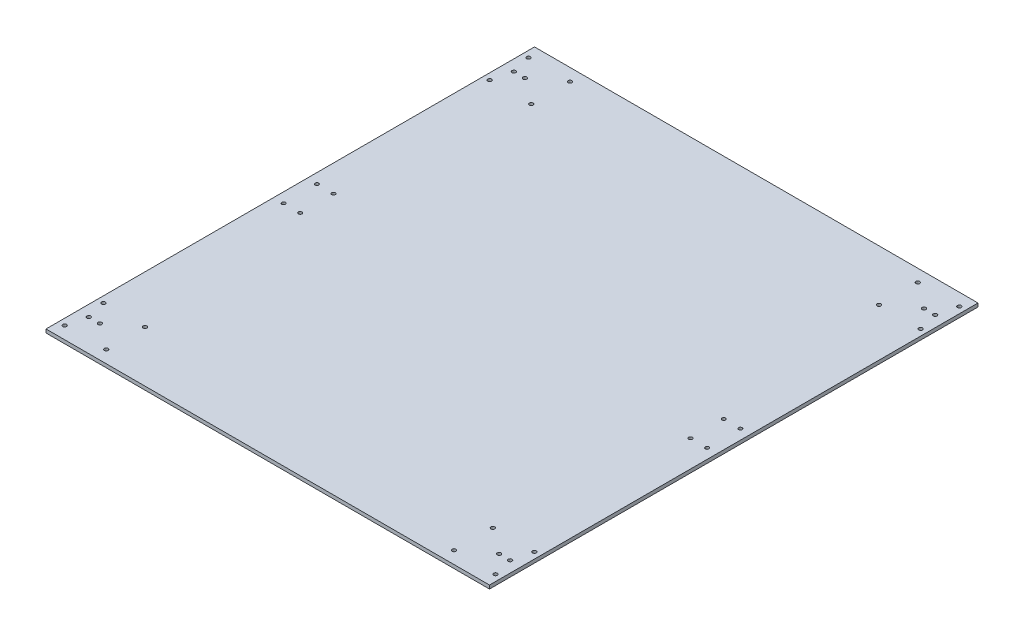
SolidWorks part; units mm, degrees
material "Acrylic (Medium-high impact)"
ref_plane "Front Plane" through (0, 0, 0) normal (0, 0, 1) x (1, 0, 0)
ref_plane "Top Plane" through (0, 0, 0) normal (0, 1, 0) x (1, 0, 0)
ref_plane "Right Plane" through (0, 0, 0) normal (1, 0, 0) x (0, 0, -1)
sketch "Sketch1" plane through (0, 0, 0) normal (0, 1, 0) x (1, 0, 0)
  line L1 (-200, 220.3) -> (200, 220.3)
  line L2 (-200, 220.3) -> (-200, -220.3)
  line L3 (-200, -220.3) -> (200, -220.3)
  line L4 (200, 220.3) -> (200, -220.3)
  line L5 (-200, 220.3) -> (200, -220.3) construction
  line L6 (-200, -220.3) -> (200, 220.3) construction
  point P0 (0, 0)
  dimension "D1" = 400
  dimension "D2" = 440.6
extrude "Boss-Extrude1" add sketch "Sketch1" along normal blind 3.175 contours L2 L3 L4 L1
sketch "Sketch2" plane through (0, 3.175, 0) normal (0, 1, 0) x (1, 0, 0)
  arc A0 (-181.7, 191.65) -> (-181.6248, 191.15) centre (-180, 191.65) ccw construction
  arc A1 (-181.6248, 192.15) -> (-181.7, 191.65) centre (-180, 191.65) ccw construction
  arc A2 (-178.3752, 192.15) -> (-181.6248, 192.15) centre (-180, 191.65) ccw construction
  arc A3 (-178.3, 191.65) -> (-178.3752, 192.15) centre (-180, 191.65) ccw construction
  arc A4 (-178.3752, 191.15) -> (-178.3, 191.65) centre (-180, 191.65) ccw construction
  arc A5 (-181.6248, 191.15) -> (-178.3752, 191.15) centre (-180, 191.65) ccw construction
  arc A6 (-188.3752, 192.15) -> (-191.6248, 192.15) centre (-190, 191.65) ccw construction
  arc A7 (-188.3, 191.65) -> (-188.3752, 192.15) centre (-190, 191.65) ccw construction
  arc A8 (-188.3752, 191.15) -> (-188.3, 191.65) centre (-190, 191.65) ccw construction
  arc A9 (-191.6248, 191.15) -> (-188.3752, 191.15) centre (-190, 191.65) ccw construction
  arc A10 (-191.7, 191.65) -> (-191.6248, 191.15) centre (-190, 191.65) ccw construction
  arc A11 (-191.6248, 192.15) -> (-191.7, 191.65) centre (-190, 191.65) ccw construction
  circle A12 centre (-156.8618, 174.15) radius 1.7 construction
  circle A13 centre (-194.3382, 174.15) radius 1.7 construction
  circle A14 centre (-156.8618, 209.15) radius 1.7 construction
  circle A15 centre (-194.3382, 209.15) radius 1.7 construction
  arc A16 (-181.7, 191.65) -> (-181.6248, 191.15) centre (-180, 191.65) ccw
  arc A17 (-181.6248, 192.15) -> (-181.7, 191.65) centre (-180, 191.65) ccw
  arc A18 (-178.3752, 192.15) -> (-181.6248, 192.15) centre (-180, 191.65) ccw
  arc A19 (-178.3, 191.65) -> (-178.3752, 192.15) centre (-180, 191.65) ccw
  arc A20 (-178.3752, 191.15) -> (-178.3, 191.65) centre (-180, 191.65) ccw
  arc A21 (-181.6248, 191.15) -> (-178.3752, 191.15) centre (-180, 191.65) ccw
  arc A22 (-188.3752, 192.15) -> (-191.6248, 192.15) centre (-190, 191.65) ccw
  arc A23 (-188.3, 191.65) -> (-188.3752, 192.15) centre (-190, 191.65) ccw
  arc A24 (-188.3752, 191.15) -> (-188.3, 191.65) centre (-190, 191.65) ccw
  arc A25 (-191.6248, 191.15) -> (-188.3752, 191.15) centre (-190, 191.65) ccw
  arc A26 (-191.7, 191.65) -> (-191.6248, 191.15) centre (-190, 191.65) ccw
  arc A27 (-191.6248, 192.15) -> (-191.7, 191.65) centre (-190, 191.65) ccw
  circle A28 centre (-156.8618, 174.15) radius 1.7
  circle A29 centre (-194.3382, 174.15) radius 1.7
  circle A30 centre (-156.8618, 209.15) radius 1.7
  circle A31 centre (-194.3382, 209.15) radius 1.7
  arc A32 (-178.3752, -192.15) -> (-178.3, -191.65) centre (-180, -191.65) ccw construction
  arc A33 (-181.6248, -192.15) -> (-178.3752, -192.15) centre (-180, -191.65) ccw construction
  arc A34 (-181.7, -191.65) -> (-181.6248, -192.15) centre (-180, -191.65) ccw construction
  arc A35 (-191.6248, -192.15) -> (-188.3752, -192.15) centre (-190, -191.65) ccw construction
  arc A36 (-188.3, -191.65) -> (-188.3752, -191.15) centre (-190, -191.65) ccw construction
  arc A37 (-188.3752, -192.15) -> (-188.3, -191.65) centre (-190, -191.65) ccw construction
  arc A38 (-191.7, -191.65) -> (-191.6248, -192.15) centre (-190, -191.65) ccw construction
  arc A39 (-191.6248, -191.15) -> (-191.7, -191.65) centre (-190, -191.65) ccw construction
  arc A40 (-178.3, -191.65) -> (-178.3752, -191.15) centre (-180, -191.65) ccw construction
  arc A41 (-181.6248, -191.15) -> (-181.7, -191.65) centre (-180, -191.65) ccw construction
  arc A42 (-178.3752, -191.15) -> (-181.6248, -191.15) centre (-180, -191.65) ccw construction
  arc A43 (-188.3752, -191.15) -> (-191.6248, -191.15) centre (-190, -191.65) ccw construction
  circle A44 centre (-156.8618, -209.15) radius 1.7 construction
  circle A45 centre (-194.3382, -209.15) radius 1.7 construction
  circle A46 centre (-156.8618, -174.15) radius 1.7 construction
  circle A47 centre (-194.3382, -174.15) radius 1.7 construction
  arc A48 (-178.3752, -192.15) -> (-178.3, -191.65) centre (-180, -191.65) ccw
  arc A49 (-181.6248, -192.15) -> (-178.3752, -192.15) centre (-180, -191.65) ccw
  arc A50 (-181.7, -191.65) -> (-181.6248, -192.15) centre (-180, -191.65) ccw
  arc A51 (-191.6248, -192.15) -> (-188.3752, -192.15) centre (-190, -191.65) ccw
  arc A52 (-188.3, -191.65) -> (-188.3752, -191.15) centre (-190, -191.65) ccw
  arc A53 (-188.3752, -192.15) -> (-188.3, -191.65) centre (-190, -191.65) ccw
  arc A54 (-191.7, -191.65) -> (-191.6248, -192.15) centre (-190, -191.65) ccw
  arc A55 (-191.6248, -191.15) -> (-191.7, -191.65) centre (-190, -191.65) ccw
  arc A56 (-178.3, -191.65) -> (-178.3752, -191.15) centre (-180, -191.65) ccw
  arc A57 (-181.6248, -191.15) -> (-181.7, -191.65) centre (-180, -191.65) ccw
  arc A58 (-178.3752, -191.15) -> (-181.6248, -191.15) centre (-180, -191.65) ccw
  arc A59 (-188.3752, -191.15) -> (-191.6248, -191.15) centre (-190, -191.65) ccw
  circle A60 centre (-156.8618, -209.15) radius 1.7
  circle A61 centre (-194.3382, -209.15) radius 1.7
  circle A62 centre (-156.8618, -174.15) radius 1.7
  circle A63 centre (-194.3382, -174.15) radius 1.7
  arc A64 (191.6248, -192.15) -> (191.7, -191.65) centre (190, -191.65) ccw construction
  arc A65 (188.3752, -192.15) -> (191.6248, -192.15) centre (190, -191.65) ccw construction
  arc A66 (188.3, -191.65) -> (188.3752, -192.15) centre (190, -191.65) ccw construction
  arc A67 (181.6248, -192.15) -> (181.7, -191.65) centre (180, -191.65) ccw construction
  arc A68 (178.3752, -192.15) -> (181.6248, -192.15) centre (180, -191.65) ccw construction
  arc A69 (178.3, -191.65) -> (178.3752, -192.15) centre (180, -191.65) ccw construction
  arc A70 (188.3752, -191.15) -> (188.3, -191.65) centre (190, -191.65) ccw construction
  arc A71 (191.7, -191.65) -> (191.6248, -191.15) centre (190, -191.65) ccw construction
  arc A72 (191.6248, -191.15) -> (188.3752, -191.15) centre (190, -191.65) ccw construction
  arc A73 (178.3752, -191.15) -> (178.3, -191.65) centre (180, -191.65) ccw construction
  arc A74 (181.7, -191.65) -> (181.6248, -191.15) centre (180, -191.65) ccw construction
  arc A75 (181.6248, -191.15) -> (178.3752, -191.15) centre (180, -191.65) ccw construction
  circle A76 centre (194.3382, -174.15) radius 1.7 construction
  circle A77 centre (156.8618, -174.15) radius 1.7 construction
  circle A78 centre (194.3382, -209.15) radius 1.7 construction
  circle A79 centre (156.8618, -209.15) radius 1.7 construction
  arc A80 (191.6248, -192.15) -> (191.7, -191.65) centre (190, -191.65) ccw
  arc A81 (188.3752, -192.15) -> (191.6248, -192.15) centre (190, -191.65) ccw
  arc A82 (188.3, -191.65) -> (188.3752, -192.15) centre (190, -191.65) ccw
  arc A83 (181.6248, -192.15) -> (181.7, -191.65) centre (180, -191.65) ccw
  arc A84 (178.3752, -192.15) -> (181.6248, -192.15) centre (180, -191.65) ccw
  arc A85 (178.3, -191.65) -> (178.3752, -192.15) centre (180, -191.65) ccw
  arc A86 (188.3752, -191.15) -> (188.3, -191.65) centre (190, -191.65) ccw
  arc A87 (191.7, -191.65) -> (191.6248, -191.15) centre (190, -191.65) ccw
  arc A88 (191.6248, -191.15) -> (188.3752, -191.15) centre (190, -191.65) ccw
  arc A89 (178.3752, -191.15) -> (178.3, -191.65) centre (180, -191.65) ccw
  arc A90 (181.7, -191.65) -> (181.6248, -191.15) centre (180, -191.65) ccw
  arc A91 (181.6248, -191.15) -> (178.3752, -191.15) centre (180, -191.65) ccw
  circle A92 centre (194.3382, -174.15) radius 1.7
  circle A93 centre (156.8618, -174.15) radius 1.7
  circle A94 centre (194.3382, -209.15) radius 1.7
  circle A95 centre (156.8618, -209.15) radius 1.7
  arc A96 (188.3752, 192.15) -> (188.3, 191.65) centre (190, 191.65) ccw construction
  arc A97 (188.3, 191.65) -> (188.3752, 191.15) centre (190, 191.65) ccw construction
  arc A98 (191.7, 191.65) -> (191.6248, 192.15) centre (190, 191.65) ccw construction
  arc A99 (191.6248, 191.15) -> (191.7, 191.65) centre (190, 191.65) ccw construction
  arc A100 (181.6248, 191.15) -> (181.7, 191.65) centre (180, 191.65) ccw construction
  arc A101 (181.7, 191.65) -> (181.6248, 192.15) centre (180, 191.65) ccw construction
  arc A102 (178.3, 191.65) -> (178.3752, 191.15) centre (180, 191.65) ccw construction
  arc A103 (178.3752, 192.15) -> (178.3, 191.65) centre (180, 191.65) ccw construction
  arc A104 (178.3752, 191.15) -> (181.6248, 191.15) centre (180, 191.65) ccw construction
  arc A105 (188.3752, 191.15) -> (191.6248, 191.15) centre (190, 191.65) ccw construction
  circle A106 centre (194.3382, 174.15) radius 1.7 construction
  circle A107 centre (194.3382, 209.15) radius 1.7 construction
  arc A108 (191.6248, 192.15) -> (188.3752, 192.15) centre (190, 191.65) ccw construction
  arc A109 (181.6248, 192.15) -> (178.3752, 192.15) centre (180, 191.65) ccw construction
  circle A110 centre (156.8618, 174.15) radius 1.7 construction
  circle A111 centre (156.8618, 209.15) radius 1.7 construction
  arc A112 (188.3752, 192.15) -> (188.3, 191.65) centre (190, 191.65) ccw
  arc A113 (188.3, 191.65) -> (188.3752, 191.15) centre (190, 191.65) ccw
  arc A114 (191.7, 191.65) -> (191.6248, 192.15) centre (190, 191.65) ccw
  arc A115 (191.6248, 191.15) -> (191.7, 191.65) centre (190, 191.65) ccw
  arc A116 (181.6248, 191.15) -> (181.7, 191.65) centre (180, 191.65) ccw
  arc A117 (181.7, 191.65) -> (181.6248, 192.15) centre (180, 191.65) ccw
  arc A118 (178.3, 191.65) -> (178.3752, 191.15) centre (180, 191.65) ccw
  arc A119 (178.3752, 192.15) -> (178.3, 191.65) centre (180, 191.65) ccw
  arc A120 (178.3752, 191.15) -> (181.6248, 191.15) centre (180, 191.65) ccw
  arc A121 (188.3752, 191.15) -> (191.6248, 191.15) centre (190, 191.65) ccw
  circle A122 centre (194.3382, 174.15) radius 1.7
  circle A123 centre (194.3382, 209.15) radius 1.7
  arc A124 (191.6248, 192.15) -> (188.3752, 192.15) centre (190, 191.65) ccw
  arc A125 (181.6248, 192.15) -> (178.3752, 192.15) centre (180, 191.65) ccw
  circle A126 centre (156.8618, 174.15) radius 1.7
  circle A127 centre (156.8618, 209.15) radius 1.7
extrude "Cut-Extrude1" cut sketch "Sketch2" against normal through all
hole_wizard "M3 Clearance Hole1" positions "Sketch4" profile "Sketch5" hole size "M3" standard "ANSI Metric" end condition through all
sketch "Sketch4" plane through (0, 0, 0) normal (0, -1, 0) x (-1, 0, 0)
  line L1 (-191, 15) -> (-176, 15)
  line L2 (-191, 15) -> (-191, -15)
  line L3 (-191, -15) -> (-176, -15)
  line L4 (-176, 15) -> (-176, -15)
  line L5 (-191, 15) -> (-176, -15) construction
  line L6 (-191, -15) -> (-176, 15) construction
  line L8 (176, 15) -> (191, 15)
  line L9 (176, 15) -> (176, -15)
  line L10 (176, -15) -> (191, -15)
  line L11 (191, 15) -> (191, -15)
  line L12 (176, 15) -> (191, -15) construction
  line L13 (176, -15) -> (191, 15) construction
  line L14 (-183.5, 0) -> (183.5, 0) construction
  line L15 (200, 220.3) -> (200, -220.3) construction
  point P2 (-176, -15)
  point P25 (-191, 15)
  point P26 (-191, -15)
  point P27 (-176, 15)
  point P29 (191, -15)
  point P48 (176, 15)
  point P49 (176, -15)
  point P50 (191, 15)
  point P76 (183.5, 0)
  point P78 (-183.5, 0)
  point P99 (0, 0)
  dimension "D1" = 30
  dimension "D2" = 15
  dimension "D3" = 9
sketch "Sketch5" plane through (176, 0, 15) normal (1, 0, 0) x (0, 0, -1)
  line L0 (0, 0) -> (0, 3.175)
  line L1 (0, 3.175) -> (1.6, 3.175)
  line L2 (1.6, 3.175) -> (1.6, 0)
  line L5 (1.6, 0) -> (0, 0)
  line L11 (0, -6.35) -> (0, 107.95) construction
  dimension "Thru Hole Dia." = 3.2
  dimension "Thru Hole Depth" = 3.175
